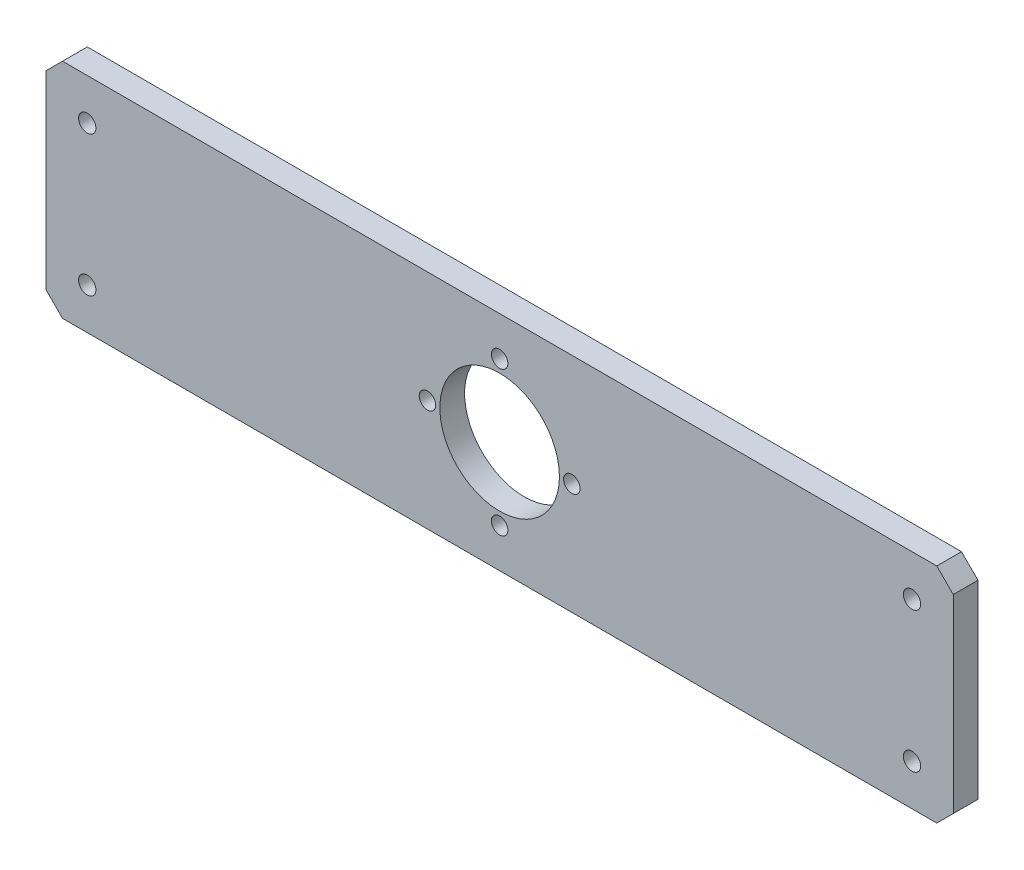
SolidWorks part; units mm, degrees
ref_plane "前视基准面" through (0, 0, 0) normal (0, 0, 1) x (1, 0, 0)
ref_plane "上视基准面" through (0, 0, 0) normal (0, 1, 0) x (1, 0, 0)
ref_plane "右视基准面" through (0, 0, 0) normal (1, 0, 0) x (0, 0, -1)
sketch "草图1" plane through (0, 0, 0) normal (0, 0, 1) x (1, 0, 0)
  line L1 (110, -27) -> (-110, -27)
  line L2 (110, -27) -> (110, 27)
  line L3 (110, 27) -> (-110, 27)
  line L4 (-110, -27) -> (-110, 27)
  line L5 (110, -27) -> (-110, 27) construction
  line L6 (110, 27) -> (-110, -27) construction
  line L7 (100, -17) -> (-100, -17) construction
  line L8 (100, -17) -> (100, 17) construction
  line L9 (100, 17) -> (-100, 17) construction
  line L10 (-100, -17) -> (-100, 17) construction
  line L11 (100, -17) -> (-100, 17) construction
  line L12 (100, 17) -> (-100, -17) construction
  circle A0 centre (-100, 17) radius 2.1
  circle A1 centre (-100, -17) radius 2.1
  circle A2 centre (100, 17) radius 2.1
  circle A3 centre (100, -17) radius 2.1
  circle A4 centre (0, 0) radius 17.5 construction
  circle A5 centre (0, 17.5) radius 2
  circle A6 centre (0, 0) radius 14.5
  circle A7 centre (17.5, 0) radius 2
  circle A8 centre (0, -17.5) radius 2
  circle A9 centre (-17.5, 0) radius 2
  point P0 (0, 0)
  point P8 (0, 0)
  point P20 (-23.563, -1.7723)
  point P21 (0, 0)
  point P29 (0, 0)
  dimension "D1" = 10
  dimension "D2" = 10
  dimension "D3" = 4.2
  dimension "D4" = 4
  dimension "D5" = 35
  dimension "D6" = 17
  dimension "D7" = 29
  dimension "D8" = 200
  dimension "D9" = 4
extrude "凸台-拉伸1" add sketch "草图1" along normal mid plane 6
chamfer "倒角1" distance 4 angle 45 4 edges at (-110, 27, 0) (-110, -27, 0) (110, -27, 0) (110, 27, 0)
